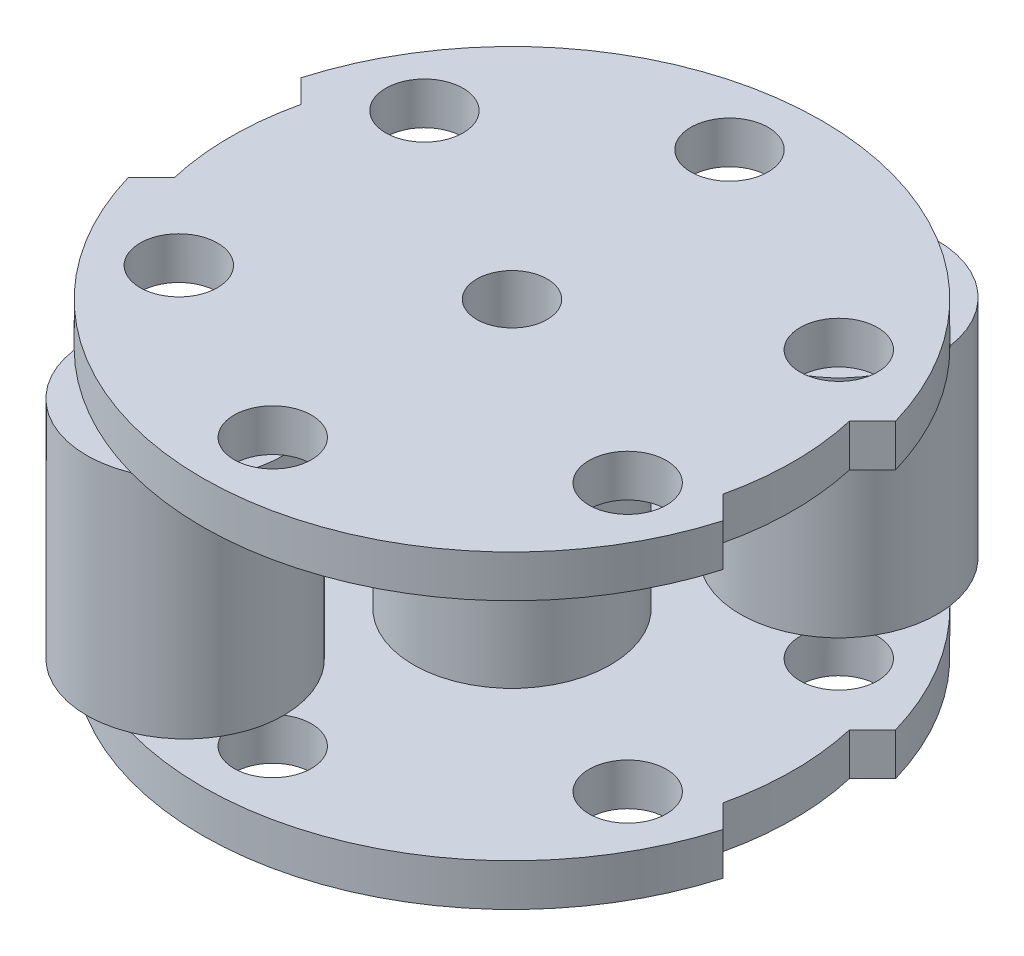
SolidWorks part; units mm, degrees
ref_plane "Front Plane" through (0, 0, 0) normal (0, 0, 1) x (1, 0, 0)
ref_plane "Top Plane" through (0, 0, 0) normal (0, 1, 0) x (1, 0, 0)
ref_plane "Right Plane" through (0, 0, 0) normal (1, 0, 0) x (0, 0, -1)
sketch "Sketch1" plane through (0, 0, 0) normal (0, 1, 0) x (1, 0, 0)
  line L0 (23.5377, 0) -> (-26.4663, 0) construction
  line L1 (0, 25.3828) -> (0, -26.7558) construction
  line L2 (19.4872, -4.5) -> (21.1261, -6.139)
  line L3 (-19.4872, -4.5) -> (-21.1261, -6.139)
  line L4 (19.4872, 4.5) -> (21.1261, 6.139)
  line L5 (-19.4872, 4.5) -> (-21.1261, 6.139)
  line L6 (-19.4872, 4.5) -> (-23.7751, 4.5) construction
  line L7 (0, 0) -> (15.4072, -7.1845) construction
  arc A0 (-21.1261, -6.139) -> (21.1261, -6.139) centre (0, 0) ccw
  circle A1 centre (0, 0) radius 7
  arc A2 (19.4872, -4.5) -> (19.4872, 4.5) centre (0, 0) ccw
  arc A3 (21.1261, 6.139) -> (-21.1261, 6.139) centre (0, 0) ccw
  arc A4 (-19.4872, 4.5) -> (-19.4872, -4.5) centre (0, 0) ccw
  circle A5 centre (0, -17) radius 2.75
  circle A6 centre (-14.7224, 8.5) radius 2.75
  circle A7 centre (14.7224, 8.5) radius 2.75
  circle A8 centre (15.4072, -7.1845) radius 2.75
  circle A9 centre (-13.9256, -9.7508) radius 2.75
  circle A10 centre (-1.4816, 16.9353) radius 2.75
  point P24 (0, 0)
  point P32 (0, 0)
  dimension "D1" = 44
  dimension "D2" = 14
  dimension "D3" = 40
  dimension "D4" = 5.5
  dimension "D8" = 5.5
  dimension "D6" = 45
  dimension "D5" = 17
  dimension "D7" = 25
  dimension "D9" = 17
extrude "Boss-Extrude1" add sketch "Sketch1" along normal blind 3
sketch "Sketch2" plane through (0, 0, 0) normal (0, -1, 0) x (1, 0, 0)
  line L0 (0, 26.4303) -> (0, -26.1308) construction
  line L1 (0, 0) -> (-8.5, 14.7224) construction
  circle A0 centre (-8.5, 14.7224) radius 7
  circle A1 centre (8.5, -14.7224) radius 7
  point P11 (0, 0)
  dimension "D2" = 14
  dimension "D1" = 30
  dimension "D3" = 17
  dimension "D4" = 2
extrude "Boss-Extrude2" add sketch "Sketch2" along normal blind 16
ref_plane "Plane1" through (0, -8, 0) normal (0, -1, 0) x (-1, 0, 0)
mirror "Mirror1" about plane through (0, -8, 0) normal (0, -1, 0) of "Boss-Extrude1"
sketch "Sketch3" plane through (0, 3, 0) normal (0, 1, 0) x (1, 0, 0)
  circle A0 centre (0, 0) radius 7
  dimension "D1" = 14
extrude "Boss-Extrude3" add sketch "Sketch3" against normal blind 26
sketch "Sketch4" plane through (0, -23, 0) normal (0, -1, 0) x (1, 0, 0)
  line L1 (1, -1) -> (1, -3.873)
  line L2 (-1, 3.873) -> (-1, 1)
  line L3 (-3.873, -1) -> (-1, -1)
  line L4 (1, 3.873) -> (1, 1)
  line L5 (-3.873, 1) -> (-1, 1)
  line L9 (1, 1) -> (3.873, 1)
  line L14 (1, -1) -> (3.873, -1)
  line L15 (-1, -1) -> (-1, -3.873)
  arc A0 (1, 3.873) -> (-1, 3.873) centre (0, 0) ccw
  arc A1 (3.873, -1) -> (3.873, 1) centre (0, 0) ccw
  arc A2 (-1, -3.873) -> (1, -3.873) centre (0, 0) ccw
  arc A3 (-3.873, 1) -> (-3.873, -1) centre (0, 0) ccw
  dimension "D1" = 8
  dimension "D2" = 2
  dimension "D3" = 2
extrude "Cut-Extrude1" cut sketch "Sketch4" against normal blind 9
sketch "Sketch5" plane through (0, -19, 0) normal (0, -1, 0) x (1, 0, 0)
  circle A0 centre (0, 0) radius 9
  circle A1 centre (0, 0) radius 7
  dimension "D1" = 18
  dimension "D2" = 14
extrude "Boss-Extrude4" add sketch "Sketch5" along normal blind 0.5
sketch "Sketch6" plane through (0, 3, 0) normal (0, 1, 0) x (1, 0, 0)
  circle A0 centre (0, 0) radius 2.5
  dimension "D1" = 5
extrude "Cut-Extrude2" cut sketch "Sketch6" against normal up to surface (17 mm away) up to face at (0, -14, 0)
